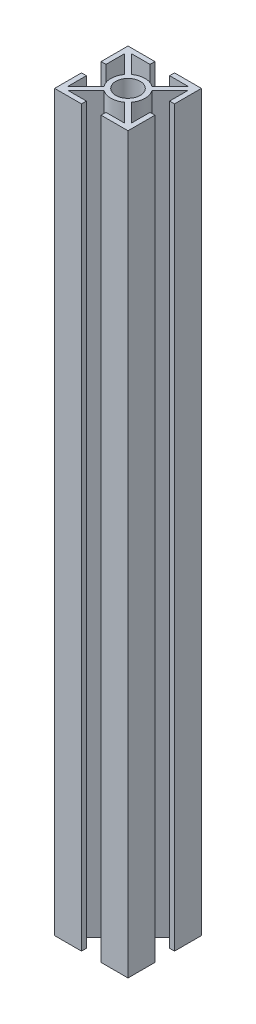
SolidWorks part; units mm, degrees
ref_plane "Front" through (0, 0, 0) normal (0, 0, 1) x (1, 0, 0)
ref_plane "Top" through (0, 0, 0) normal (0, 1, 0) x (1, 0, 0)
ref_plane "Right" through (0, 0, 0) normal (1, 0, 0) x (0, 0, -1)
sketch "Sketch1" plane through (0, 0, 0) normal (0, 1, 0) x (1, 0, 0)
  line L0 (-11.268, -11.268) -> (15.0013, 15.0013) construction
  line L1 (-14.2237, 14.2237) -> (18.9918, -18.9918) construction
  line L2 (4.1919, 5.6061) -> (11.5871, 13.0013)
  line L3 (-6.0914, 0) -> (9.94, 0) construction
  line L4 (13.0013, 11.5871) -> (5.6061, 4.1919)
  line L5 (15.0013, 15.0013) -> (4.0013, 15.0013)
  line L6 (4.0013, 15.0013) -> (4.0013, 13.0013)
  line L7 (4.0013, 13.0013) -> (11.5871, 13.0013)
  line L8 (15.0013, 15.0013) -> (15.0013, 4.0013)
  line L9 (15.0013, 4.0013) -> (13.0013, 4.0013)
  line L10 (13.0013, 4.0013) -> (13.0013, 11.5871)
  line L11 (0, 3.6644) -> (0, -12.3399) construction
  line L12 (4.0013, -13.0013) -> (11.5871, -13.0013)
  line L13 (4.0013, -15.0013) -> (4.0013, -13.0013)
  line L14 (15.0013, -15.0013) -> (4.0013, -15.0013)
  line L15 (15.0013, -15.0013) -> (15.0013, -4.0013)
  line L16 (15.0013, -4.0013) -> (13.0013, -4.0013)
  line L17 (13.0013, -4.0013) -> (13.0013, -11.5871)
  line L18 (13.0013, -11.5871) -> (5.6061, -4.1919)
  line L19 (4.1919, -5.6061) -> (11.5871, -13.0013)
  line L20 (-13.0013, 11.5871) -> (-5.6061, 4.1919)
  line L21 (-4.1919, 5.6061) -> (-11.5871, 13.0013)
  line L22 (-15.0013, 4.0013) -> (-13.0013, 4.0013)
  line L23 (-13.0013, 4.0013) -> (-13.0013, 11.5871)
  line L24 (-15.0013, 15.0013) -> (-15.0013, 4.0013)
  line L25 (-4.0013, 13.0013) -> (-11.5871, 13.0013)
  line L26 (-4.0013, 15.0013) -> (-4.0013, 13.0013)
  line L27 (-15.0013, 15.0013) -> (-4.0013, 15.0013)
  line L28 (-4.1919, -5.6061) -> (-11.5871, -13.0013)
  line L29 (-15.0013, -4.0013) -> (-13.0013, -4.0013)
  line L30 (-13.0013, -4.0013) -> (-13.0013, -11.5871)
  line L31 (-13.0013, -11.5871) -> (-5.6061, -4.1919)
  line L32 (-15.0013, -15.0013) -> (-15.0013, -4.0013)
  line L33 (-15.0013, -15.0013) -> (-4.0013, -15.0013)
  line L34 (-4.0013, -15.0013) -> (-4.0013, -13.0013)
  line L35 (-4.0013, -13.0013) -> (-11.5871, -13.0013)
  arc A0 (4.1919, 5.6061) -> (-4.1919, 5.6061) centre (0, 0) ccw
  circle A1 centre (0, 0) radius 5
  arc A2 (-5.6061, 4.1919) -> (-5.6061, -4.1919) centre (0, 0) ccw
  arc A3 (-4.1919, -5.6061) -> (4.1919, -5.6061) centre (0, 0) ccw
  arc A4 (5.6061, -4.1919) -> (5.6061, 4.1919) centre (0, 0) ccw
  point P9 (14.0013, 4.0013)
  point P12 (4.0013, 14.0013)
  point P21 (4.0013, -14.0013)
  point P27 (14.0013, -4.0013)
  dimension "D1" = 14
  dimension "D2" = 90
  dimension "D6" = 10
  dimension "D3" = 21.215
  dimension "D4" = 11
  dimension "D5" = 11
  dimension "D7" = 2
  dimension "D8" = 1
  dimension "D9" = 2
  dimension "D10" = 2
  dimension "D11" = 45
extrude "Boss-Extrude1" add sketch "Sketch1" along normal blind 300
